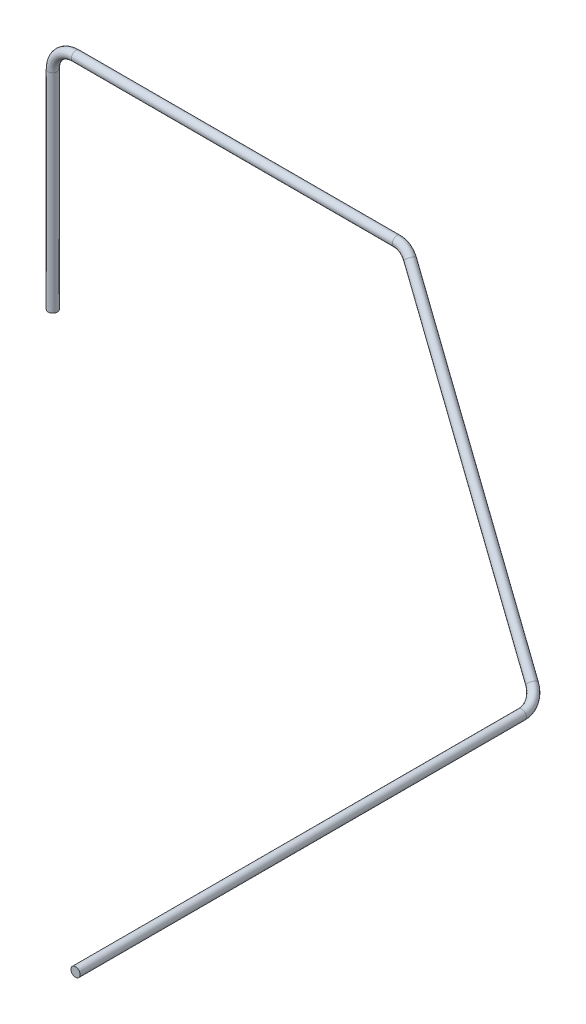
SolidWorks part; units mm, degrees
ref_plane "Front Plane" through (0, 0, 0) normal (0, 0, 1) x (1, 0, 0)
ref_plane "Top Plane" through (0, 0, 0) normal (0, 1, 0) x (1, 0, 0)
ref_plane "Right Plane" through (0, 0, 0) normal (1, 0, 0) x (0, 0, -1)
sketch3d "3DSketch1"
  line L0 (0, 0, 0) -> (0, 90, 0)
  line L1 (10, 100, 0) -> (148.7408, 100, 0)
  line L2 (155.8119, 97.4043, 1.3568) -> (253.9164, 10.4606, 46.8023)
  line L3 (258.9489, 6.0006, 56.2506) -> (258.9489, 6.0006, 249.1336)
  arc A0 (253.9164, 10.4606, 46.8023) -> (258.9489, 6.0006, 56.2506) centre (251.465, 12.6331, 56.2506) ccw
  arc A1 (155.8119, 97.4043, 1.3568) -> (148.7408, 100, 0) centre (148.7408, 91.1376, 4.6324) ccw
  arc A2 (10, 100, 0) -> (0, 90, 0) centre (10, 90, 0) ccw
  point P6 (256.3114, -6.0006, 203.7255)
  point P13 (258.9489, 6.0006, 49.1336)
  point P14 (244.8325, 5.1492, 56.2506)
  point P17 (152.8829, 100, 0)
  point P18 (148.7408, 95.77, 13.4947)
  point P21 (0, 100, 0)
  point P22 (10, 90, 10)
  dimension "D6" = 10
  dimension "D1" = 100
  dimension "D2" = 150
  dimension "D3" = 200
  dimension "D4" = 45
  dimension "D5" = 6.0006
sketch "Sketch1" plane through (0, 0, 0) normal (0, 0, -1) x (1, 0, 0)
  line L0 (0, 0) -> (0, -60)
  line L1 (20, -80) -> (53.4315, -80)
  line L2 (67.5736, -74.1421) -> (91.2132, -50.5025)
  line L3 (97.0711, -36.3604) -> (97.0711, -19.6447)
  arc A0 (97.0711, -36.3604) -> (91.2132, -50.5025) centre (77.0711, -36.3604) cw
  arc A1 (67.5736, -74.1421) -> (53.4315, -80) centre (53.4315, -60) cw
  arc A2 (20, -80) -> (0, -60) centre (20, -60) cw
  point P8 (97.0711, -44.6447)
  point P12 (61.7157, -80)
  point P15 (0, -80)
  dimension "D2" = 25
  dimension "D3" = 50
  dimension "D5" = 20
  dimension "D1" = 80
  dimension "D4" = 45
sketch "Sketch2" plane through (0, 0, 0) normal (0, 1, 0) x (1, 0, 0)
  circle A0 centre (0, 0) radius 2
  dimension "D1" = 4
sweep "Sweep1" add profiles "Sketch2" path "3DSketch1"
